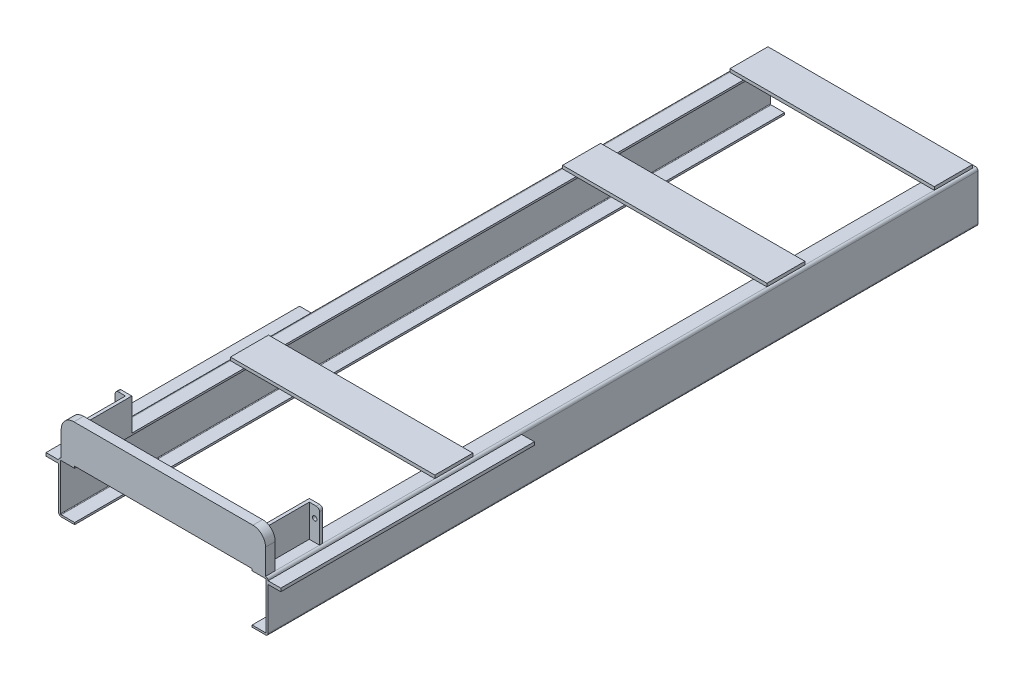
SolidWorks part; units mm, degrees
ref_plane "Front Plane" through (0, 0, 0) normal (0, 0, 1) x (1, 0, 0)
ref_plane "Top Plane" through (0, 0, 0) normal (0, 1, 0) x (1, 0, 0)
ref_plane "Right Plane" through (0, 0, 0) normal (1, 0, 0) x (0, 0, -1)
sketch "Sketch1" plane through (0, 0, 0) normal (0, 0, 1) x (1, 0, 0)
  line L0 (0, 0) -> (413, 0) construction
  line L1 (350, 100) -> (403, 100)
  line L2 (413, 90) -> (413, -90)
  line L3 (403, -100) -> (350, -100)
  arc A0 (413, -90) -> (403, -100) centre (403, -90) cw
  arc A1 (403, 100) -> (413, 90) centre (403, 90) cw
  point P5 (0, 0)
  point P10 (413, -100)
  point P13 (413, 100)
  dimension "D4" = 10
  dimension "D1" = 413
  dimension "D2" = 200
  dimension "D3" = 63
extrude "Extrude-Thin1" add sketch "Sketch1" along normal mid plane 2800 thin
sketch "Sketch2" plane through (0, 0, 1400) normal (0, 0, 1) x (1, 0, 0)
  line L1 (413, 90) -> (463, 90)
  line L2 (413, 90) -> (413, 77.5)
  line L3 (413, 77.5) -> (463, 77.5)
  line L4 (463, 90) -> (463, 77.5)
  dimension "D1" = 50
  dimension "D2" = 12.5
extrude "Boss-Extrude1" add sketch "Sketch2" against normal blind 1000
mirror "Mirror2" about plane through (0, 0, 0) normal (1, 0, 0) of bodies 102
sketch "Sketch3" plane through (0, 0, 1400) normal (0, 0, 1) x (1, 0, 0)
  line L1 (-403, 100) -> (403, 100)
  line L2 (-403, 100) -> (-403, 200)
  line L3 (-353, 250) -> (353, 250)
  line L4 (403, 100) -> (403, 200)
  arc A0 (353, 250) -> (403, 200) centre (353, 200) cw
  arc A1 (-403, 200) -> (-353, 250) centre (-353, 200) cw
  point P5 (0, 0)
  point P9 (403, 250)
  dimension "D2" = 50
  dimension "D1" = 150
extrude "Boss-Extrude2" add sketch "Sketch3" against normal blind 38
sketch "Sketch4" plane through (0, 100, 0) normal (0, 1, 0) x (1, 0, 0)
  line L0 (-403, -1362) -> (-403, 1400) construction
  line L1 (-403, 1387.5) -> (403, 1387.5)
  line L2 (-403, 1387.5) -> (-403, 1237.5)
  line L3 (-403, 1237.5) -> (403, 1237.5)
  line L4 (403, 1387.5) -> (403, 1237.5)
  line L5 (403, -1362) -> (403, 1400) construction
  line L6 (350, 1400) -> (403, 1400) construction
  dimension "D1" = 150
  dimension "D2" = 12.5
extrude "Boss-Extrude3" add sketch "Sketch4" along normal blind 12.5
pattern_linear "LPattern1" count 2 spacing 660 along (0, 0, 1) of "Boss-Extrude3"
pattern_linear "LPattern2" count 2 spacing 1970 along (0, 0, 1) of "Boss-Extrude3"
sketch "Sketch5" plane through (0, 0, 1362) normal (0, 0, -1) x (-1, 0, 0)
  line L1 (-350, 100) -> (-362.5, 100)
  line L2 (-350, 100) -> (-350, 227)
  line L3 (-350, 227) -> (-362.5, 227)
  line L4 (-362.5, 100) -> (-362.5, 227)
  dimension "D1" = 127
  dimension "D2" = 12.5
extrude "Boss-Extrude4" add sketch "Sketch5" along normal blind 175
sketch "Sketch6" plane through (0, 0, 1187) normal (0, 0, -1) x (-1, 0, 0)
  line L1 (-350, 100) -> (-403, 100)
  line L2 (-350, 100) -> (-350, 227)
  line L3 (-350, 227) -> (-403, 227)
  line L4 (-403, 100) -> (-403, 227)
  circle A0 centre (-384, 182) radius 8.75
  dimension "D1" = 17.5
  dimension "D2" = 82
  dimension "D3" = 19
extrude "Boss-Extrude5" add sketch "Sketch6" along normal blind 12.5
fillet "Fillet1" radius 12.5 1 edges at (403, 227, 1180.75)
mirror "Mirror3" about plane through (0, 0, 0) normal (1, 0, 0) of "Boss-Extrude4", "Boss-Extrude5", "Fillet1"
